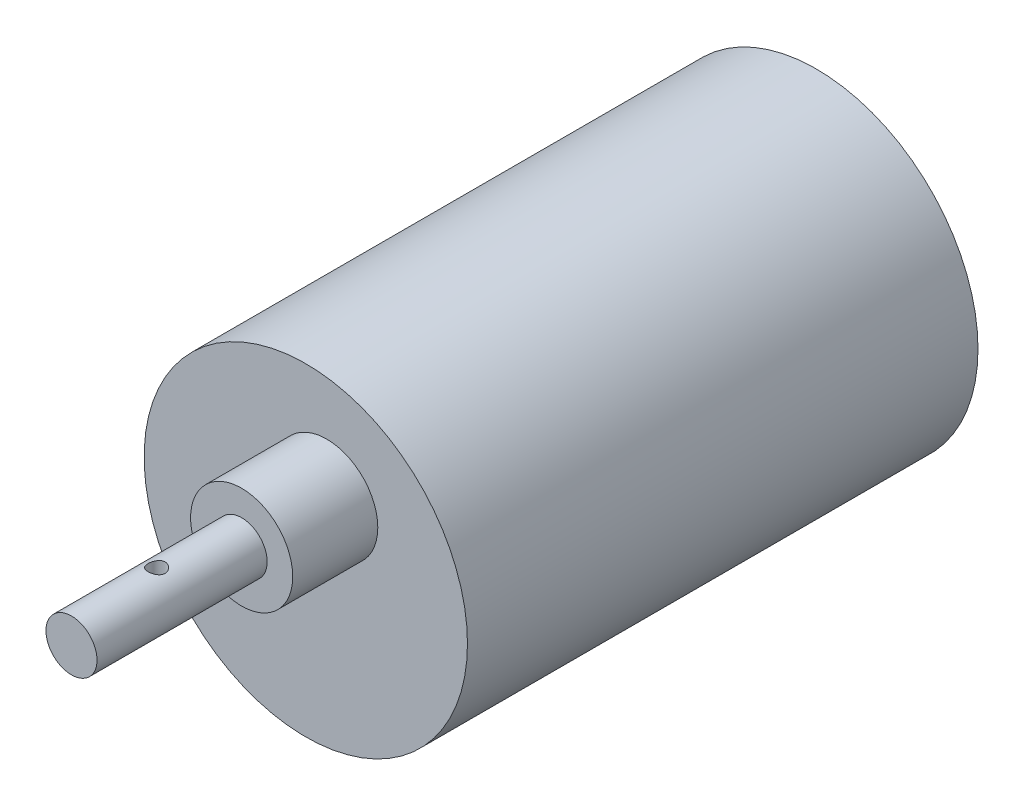
SolidWorks part; units mm, degrees
ref_plane "Front Plane" through (0, 0, 0) normal (0, 0, 1) x (1, 0, 0)
ref_plane "Top Plane" through (0, 0, 0) normal (0, 1, 0) x (1, 0, 0)
ref_plane "Right Plane" through (0, 0, 0) normal (1, 0, 0) x (0, 0, -1)
sketch "Sketch1" plane through (0, 0, 0) normal (0, 0, 1) x (1, 0, 0)
  circle A0 centre (0, 0) radius 19
  dimension "D1" = 38
extrude "motor machinery" add sketch "Sketch1" along normal blind 60
sketch "Sketch2" plane through (0, 0, 60) normal (0, 0, 1) x (1, 0, 0)
  circle A0 centre (2.4596, 6.5537) radius 6
  dimension "D1" = 12
  dimension "D2" = 7
extrude "Boss-Extrude2" add sketch "Sketch2" along normal blind 10
sketch "Sketch5" plane through (0, 0, 70) normal (0, 0, 1) x (1, 0, 0)
  line L0 (2.4596, 12.5537) -> (2.4596, 6.5537) construction
  circle A0 centre (2.4596, 6.5537) radius 6 construction
  circle A1 centre (2.4596, 6.5537) radius 6 construction
  circle A2 centre (2.4596, 6.5537) radius 3
  dimension "D1" = 6
extrude "motor shaft" add sketch "Sketch5" along normal blind 20
sketch "Sketch7" plane through (0, 0, 0) normal (0, 1, 0) x (1, 0, 0)
  line L0 (2.4596, -90) -> (2.4596, -82.2208) construction
  line L1 (-0.5404, -90) -> (5.4596, -90) construction
  circle A0 centre (2.4596, -80) radius 1
  dimension "D1" = 2
  dimension "D2" = 10
extrude "hub holes" cut sketch "Sketch7" along normal blind 20
